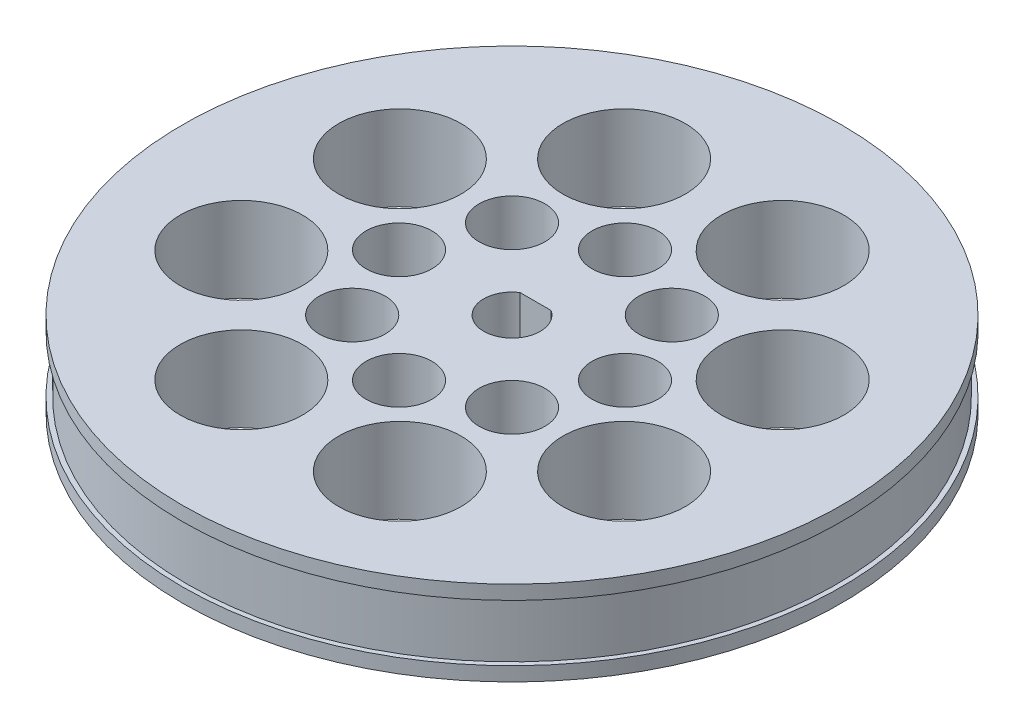
SolidWorks part; units mm, degrees
ref_plane "정면" through (0, 0, 0) normal (0, 0, 1) x (1, 0, 0)
ref_plane "윗면" through (0, 0, 0) normal (0, 1, 0) x (1, 0, 0)
ref_plane "우측면" through (0, 0, 0) normal (1, 0, 0) x (0, 0, -1)
sketch "스케치1" plane through (0, 0, 0) normal (0, 1, 0) x (1, 0, 0)
  circle A0 centre (0, 0) radius 35
  dimension "D1" = 70
extrude "보스-돌출1" add sketch "스케치1" along normal blind 9
sketch "스케치2" plane through (0, 9, 0) normal (0, 1, 0) x (1, 0, 0)
  line L0 (-1.6583, 2.5) -> (1.6583, 2.5)
  arc A0 (-1.6583, 2.5) -> (1.6583, 2.5) centre (0, 0) ccw
  dimension "D1" = 6
  dimension "D2" = 2.5
extrude "컷-돌출1" cut sketch "스케치2" against normal through all both and the other way through all contours A0 L0
sketch "스케치3" plane through (0, 9, 0) normal (0, 1, 0) x (1, 0, 0)
  line L0 (-12.0332, 0) -> (11.8799, 0) construction
  line L1 (0, -14.784) -> (0, 18.0482) construction
  line L2 (-12.0414, 12.0414) -> (12.4107, -12.4107) construction
  line L3 (-11.7487, -11.7487) -> (17.1029, 17.1029) construction
  line L4 (8.419, -20.3253) -> (0, 0) construction
  circle A0 centre (8.4853, -8.4853) radius 3.5
  circle A1 centre (8.419, -20.3253) radius 6.5
  circle A2 centre (-8.419, -20.3253) radius 6.5
  circle A3 centre (0, -12) radius 3.5
  circle A4 centre (-20.3253, -8.419) radius 6.5
  circle A5 centre (-8.4853, -8.4853) radius 3.5
  circle A6 centre (-20.3253, 8.419) radius 6.5
  circle A7 centre (-12, 0) radius 3.5
  circle A8 centre (-8.419, 20.3253) radius 6.5
  circle A9 centre (-8.4853, 8.4853) radius 3.5
  circle A10 centre (8.419, 20.3253) radius 6.5
  circle A11 centre (0, 12) radius 3.5
  circle A12 centre (20.3253, 8.419) radius 6.5
  circle A13 centre (8.4853, 8.4853) radius 3.5
  circle A14 centre (20.3253, -8.419) radius 6.5
  circle A15 centre (12, 0) radius 3.5
  point P44 (0, 0)
  dimension "D4" = 13
  dimension "D6" = 7
  dimension "D1" = 45
  dimension "D2" = 45
  dimension "D3" = 22
  dimension "D5" = 12
  dimension "D7" = 22.5
  dimension "D8" = 8
extrude "컷-돌출2" cut sketch "스케치3" against normal through all both and the other way through all
sketch "스케치4" plane through (0, 0, 0) normal (1, 0, 0) x (0, 0, -1)
  line L0 (35, 0) -> (35, 9) construction
  line L1 (34.5, 7.5) -> (35.5, 7.5)
  line L2 (34.5, 7.5) -> (34.5, 1.5)
  line L3 (34.5, 1.5) -> (35.5, 1.5)
  line L4 (35.5, 7.5) -> (35.5, 1.5)
  line L5 (34.5, 7.5) -> (35.5, 1.5) construction
  line L6 (34.5, 1.5) -> (35.5, 7.5) construction
  line L7 (38.4873, 0) -> (32.429, 0) construction
  line L8 (35, 0) -> (35, 9) construction
  line L9 (38.6962, 4.5) -> (32.0982, 4.5) construction
  line L10 (-35, 0) -> (35, 0) construction
  line L11 (35, 9) -> (-35, 9) construction
  point P0 (35, 4.5)
  dimension "D1" = 6
  dimension "D2" = 4.5
  dimension "D3" = 0.5
revolve "컷-회전1" cut sketch "스케치4" angle 360 about axis through (0, 9, 0) along (0, -1, 0)
